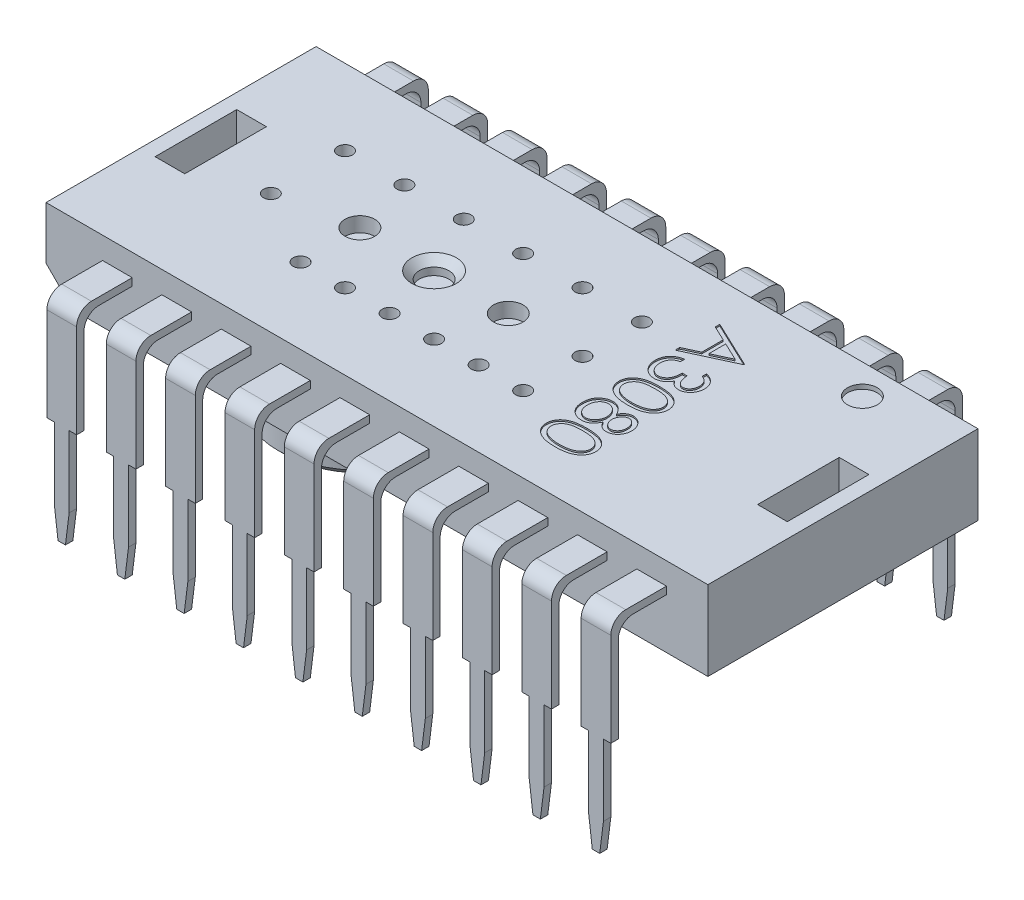
SolidWorks part; units mm, degrees
ref_plane "Front Plane" through (0, 0, 0) normal (0, 0, 1) x (1, 0, 0)
ref_plane "Top Plane" through (0, 0, 0) normal (0, 1, 0) x (1, 0, 0)
ref_plane "Right Plane" through (0, 0, 0) normal (1, 0, 0) x (0, 0, -1)
sketch "Sketch1" plane through (0, 0, 0) normal (0, 1, 0) x (1, 0, 0)
  line L1 (0, 0) -> (22.3, 0)
  line L2 (0, 0) -> (0, 9.1)
  line L3 (0, 9.1) -> (22.3, 9.1)
  line L4 (22.3, 0) -> (22.3, 9.1)
  dimension "D1" = 22.3
  dimension "D2" = 9.1
extrude "Boss-Extrude1" add sketch "Sketch1" along normal blind 3.18
sketch "Sketch2" plane through (0, 0, 0) normal (0, -1, 0) x (-1, 0, 0)
  line L0 (0, 4.55) -> (-22.3, 4.55) construction
  line L1 (0, 9.1) -> (0, 0) construction
  line L2 (-22.3, 0) -> (-22.3, 9.1) construction
  circle A0 centre (-6.025, 4.55) radius 2.8
  circle A1 centre (-6.025, 4.55) radius 0.525
  dimension "D1" = 5.6
  dimension "D3" = 1.05
  dimension "D2" = 6.025
extrude "Boss-Extrude2" add sketch "Sketch2" along normal blind 2.25 draft 1.5
chamfer "Chamfer1" distance 0.3 angle 45 1 edges at (6.025, -2.25, -7.2911)
ref_plane "Plane1" through (0, 2.19, 0) normal (0, 1, 0) x (1, 0, 0)
sketch "Sketch3" plane through (0, 2.19, 0) normal (0, 1, 0) x (1, 0, 0)
  line L0 (18.905, 9.1) -> (18.905, 10.975)
  line L1 (22.3, 9.1) -> (0, 9.1) construction
  line L2 (18.905, 10.975) -> (19.905, 10.975)
  line L3 (19.905, 10.975) -> (19.905, 9.1)
  line L4 (16.905, 9.1) -> (16.905, 10.975)
  line L5 (16.905, 10.975) -> (17.905, 10.975)
  line L6 (17.905, 10.975) -> (17.905, 9.1)
  line L7 (14.905, 9.1) -> (14.905, 10.975)
  line L8 (14.905, 10.975) -> (15.905, 10.975)
  line L9 (15.905, 10.975) -> (15.905, 9.1)
  line L10 (12.905, 9.1) -> (12.905, 10.975)
  line L11 (12.905, 10.975) -> (13.905, 10.975)
  line L12 (13.905, 10.975) -> (13.905, 9.1)
  line L13 (10.905, 9.1) -> (10.905, 10.975)
  line L14 (10.905, 10.975) -> (11.905, 10.975)
  line L15 (11.905, 10.975) -> (11.905, 9.1)
  line L16 (8.905, 9.1) -> (8.905, 10.975)
  line L17 (8.905, 10.975) -> (9.905, 10.975)
  line L18 (9.905, 10.975) -> (9.905, 9.1)
  line L19 (6.905, 9.1) -> (6.905, 10.975)
  line L20 (6.905, 10.975) -> (7.905, 10.975)
  line L21 (7.905, 10.975) -> (7.905, 9.1)
  line L22 (4.905, 9.1) -> (4.905, 10.975)
  line L23 (4.905, 10.975) -> (5.905, 10.975)
  line L24 (5.905, 10.975) -> (5.905, 9.1)
  line L25 (2.905, 9.1) -> (2.905, 10.975)
  line L26 (2.905, 10.975) -> (3.905, 10.975)
  line L27 (3.905, 10.975) -> (3.905, 9.1)
  line L28 (0.905, 9.1) -> (0.905, 10.975)
  line L29 (0.905, 10.975) -> (1.905, 10.975)
  line L30 (1.905, 10.975) -> (1.905, 9.1)
  line L31 (0, 0) -> (22.3, 0) construction
  line L32 (20.905, 0) -> (19.905, 0)
  line L33 (20.905, 0) -> (20.905, -1.875)
  line L34 (20.905, -1.875) -> (19.905, -1.875)
  line L35 (19.905, 0) -> (19.905, -1.875)
  line L36 (18.905, 0) -> (17.905, 0)
  line L37 (18.905, 0) -> (18.905, -1.875)
  line L38 (18.905, -1.875) -> (17.905, -1.875)
  line L39 (17.905, 0) -> (17.905, -1.875)
  line L40 (16.905, 0) -> (15.905, 0)
  line L41 (16.905, 0) -> (16.905, -1.875)
  line L42 (16.905, -1.875) -> (15.905, -1.875)
  line L43 (15.905, 0) -> (15.905, -1.875)
  line L44 (14.905, 0) -> (13.905, 0)
  line L45 (14.905, 0) -> (14.905, -1.875)
  line L46 (14.905, -1.875) -> (13.905, -1.875)
  line L47 (13.905, 0) -> (13.905, -1.875)
  line L48 (12.905, 0) -> (11.905, 0)
  line L49 (12.905, 0) -> (12.905, -1.875)
  line L50 (12.905, -1.875) -> (11.905, -1.875)
  line L51 (11.905, 0) -> (11.905, -1.875)
  line L52 (10.905, 0) -> (9.905, 0)
  line L53 (10.905, 0) -> (10.905, -1.875)
  line L54 (10.905, -1.875) -> (9.905, -1.875)
  line L55 (9.905, 0) -> (9.905, -1.875)
  line L56 (8.905, 0) -> (7.905, 0)
  line L57 (8.905, 0) -> (8.905, -1.875)
  line L58 (8.905, -1.875) -> (7.905, -1.875)
  line L59 (7.905, 0) -> (7.905, -1.875)
  line L60 (6.905, 0) -> (5.905, 0)
  line L61 (6.905, 0) -> (6.905, -1.875)
  line L62 (6.905, -1.875) -> (5.905, -1.875)
  line L63 (5.905, 0) -> (5.905, -1.875)
  line L64 (4.905, 0) -> (3.905, 0)
  line L65 (4.905, 0) -> (4.905, -1.875)
  line L66 (4.905, -1.875) -> (3.905, -1.875)
  line L67 (3.905, 0) -> (3.905, -1.875)
  line L68 (2.905, 0) -> (1.905, 0)
  line L69 (2.905, 0) -> (2.905, -1.875)
  line L70 (2.905, -1.875) -> (1.905, -1.875)
  line L71 (1.905, 0) -> (1.905, -1.875)
  line L72 (19.905, 9.1) -> (18.905, 9.1)
  line L73 (17.905, 9.1) -> (16.905, 9.1)
  line L74 (1.905, 9.1) -> (0.905, 9.1)
  line L75 (3.905, 9.1) -> (2.905, 9.1)
  line L76 (5.905, 9.1) -> (4.905, 9.1)
  line L77 (7.905, 9.1) -> (6.905, 9.1)
  line L78 (9.905, 9.1) -> (8.905, 9.1)
  line L79 (11.905, 9.1) -> (10.905, 9.1)
  line L80 (13.905, 9.1) -> (12.905, 9.1)
  line L81 (15.905, 9.1) -> (14.905, 9.1)
  circle A0 centre (6.025, 4.55) radius 0.525 construction
  point P6 (19.405, 10.975)
  point P51 (20.405, 0)
  dimension "D1" = 1.875
  dimension "D2" = 1
  dimension "D3" = 13.38
  dimension "D5" = 1.875
  dimension "D6" = 1
  dimension "D7" = 1
  dimension "D4" = 10
  dimension "D8" = 10
extrude "Boss-Extrude3" add sketch "Sketch3" along normal blind 0.25
sketch "Sketch5" plane through (0, 0, 1.875) normal (0, 0, 1) x (1, 0, 0)
  line L0 (2.905, 2.44) -> (1.905, 2.44) construction
  line L1 (1.905, 2.19) -> (2.905, 2.19)
  line L2 (1.905, 2.19) -> (1.905, -1.21)
  line L3 (2.155, -4.61) -> (2.655, -4.61)
  line L4 (2.905, 2.19) -> (2.905, -1.21)
  line L5 (1.905, -1.21) -> (2.155, -1.21)
  line L6 (0, 0) -> (22.3, 0) construction
  line L7 (2.405, 2.19) -> (2.405, -4.61) construction
  line L8 (2.155, -1.21) -> (2.155, -4.61)
  line L9 (2.655, -1.21) -> (2.655, -4.61)
  line L10 (2.655, -1.21) -> (2.905, -1.21)
  line L11 (3.905, 2.19) -> (4.905, 2.19)
  line L12 (3.905, 2.19) -> (3.905, -1.21)
  line L13 (4.155, -4.61) -> (4.655, -4.61)
  line L14 (4.905, 2.19) -> (4.905, -1.21)
  line L15 (3.905, -1.21) -> (4.155, -1.21)
  line L16 (4.155, -1.21) -> (4.155, -4.61)
  line L17 (4.655, -1.21) -> (4.655, -4.61)
  line L18 (4.655, -1.21) -> (4.905, -1.21)
  line L19 (4.405, 2.19) -> (4.405, -4.61) construction
  line L20 (5.905, 2.19) -> (6.905, 2.19)
  line L21 (5.905, 2.19) -> (5.905, -1.21)
  line L22 (6.155, -4.61) -> (6.655, -4.61)
  line L23 (6.905, 2.19) -> (6.905, -1.21)
  line L24 (5.905, -1.21) -> (6.155, -1.21)
  line L25 (6.155, -1.21) -> (6.155, -4.61)
  line L26 (6.655, -1.21) -> (6.655, -4.61)
  line L27 (6.655, -1.21) -> (6.905, -1.21)
  line L28 (6.405, 2.19) -> (6.405, -4.61) construction
  line L29 (7.905, 2.19) -> (8.905, 2.19)
  line L30 (7.905, 2.19) -> (7.905, -1.21)
  line L31 (8.155, -4.61) -> (8.655, -4.61)
  line L32 (8.905, 2.19) -> (8.905, -1.21)
  line L33 (7.905, -1.21) -> (8.155, -1.21)
  line L34 (8.155, -1.21) -> (8.155, -4.61)
  line L35 (8.655, -1.21) -> (8.655, -4.61)
  line L36 (8.655, -1.21) -> (8.905, -1.21)
  line L37 (8.405, 2.19) -> (8.405, -4.61) construction
  line L38 (9.905, 2.19) -> (10.905, 2.19)
  line L39 (9.905, 2.19) -> (9.905, -1.21)
  line L40 (10.155, -4.61) -> (10.655, -4.61)
  line L41 (10.905, 2.19) -> (10.905, -1.21)
  line L42 (9.905, -1.21) -> (10.155, -1.21)
  line L43 (10.155, -1.21) -> (10.155, -4.61)
  line L44 (10.655, -1.21) -> (10.655, -4.61)
  line L45 (10.655, -1.21) -> (10.905, -1.21)
  line L46 (10.405, 2.19) -> (10.405, -4.61) construction
  line L47 (11.905, 2.19) -> (12.905, 2.19)
  line L48 (11.905, 2.19) -> (11.905, -1.21)
  line L49 (12.155, -4.61) -> (12.655, -4.61)
  line L50 (12.905, 2.19) -> (12.905, -1.21)
  line L51 (11.905, -1.21) -> (12.155, -1.21)
  line L52 (12.155, -1.21) -> (12.155, -4.61)
  line L53 (12.655, -1.21) -> (12.655, -4.61)
  line L54 (12.655, -1.21) -> (12.905, -1.21)
  line L55 (12.405, 2.19) -> (12.405, -4.61) construction
  line L56 (13.905, 2.19) -> (14.905, 2.19)
  line L57 (13.905, 2.19) -> (13.905, -1.21)
  line L58 (14.155, -4.61) -> (14.655, -4.61)
  line L59 (14.905, 2.19) -> (14.905, -1.21)
  line L60 (13.905, -1.21) -> (14.155, -1.21)
  line L61 (14.155, -1.21) -> (14.155, -4.61)
  line L62 (14.655, -1.21) -> (14.655, -4.61)
  line L63 (14.655, -1.21) -> (14.905, -1.21)
  line L64 (14.405, 2.19) -> (14.405, -4.61) construction
  line L65 (15.905, 2.19) -> (16.905, 2.19)
  line L66 (15.905, 2.19) -> (15.905, -1.21)
  line L67 (16.155, -4.61) -> (16.655, -4.61)
  line L68 (16.905, 2.19) -> (16.905, -1.21)
  line L69 (15.905, -1.21) -> (16.155, -1.21)
  line L70 (16.155, -1.21) -> (16.155, -4.61)
  line L71 (16.655, -1.21) -> (16.655, -4.61)
  line L72 (16.655, -1.21) -> (16.905, -1.21)
  line L73 (16.405, 2.19) -> (16.405, -4.61) construction
  line L74 (17.905, 2.19) -> (18.905, 2.19)
  line L75 (17.905, 2.19) -> (17.905, -1.21)
  line L76 (18.155, -4.61) -> (18.655, -4.61)
  line L77 (18.905, 2.19) -> (18.905, -1.21)
  line L78 (17.905, -1.21) -> (18.155, -1.21)
  line L79 (18.155, -1.21) -> (18.155, -4.61)
  line L80 (18.655, -1.21) -> (18.655, -4.61)
  line L81 (18.655, -1.21) -> (18.905, -1.21)
  line L82 (18.405, 2.19) -> (18.405, -4.61) construction
  line L83 (19.905, 2.19) -> (20.905, 2.19)
  line L84 (19.905, 2.19) -> (19.905, -1.21)
  line L85 (20.155, -4.61) -> (20.655, -4.61)
  line L86 (20.905, 2.19) -> (20.905, -1.21)
  line L87 (19.905, -1.21) -> (20.155, -1.21)
  line L88 (20.155, -1.21) -> (20.155, -4.61)
  line L89 (20.655, -1.21) -> (20.655, -4.61)
  line L90 (20.655, -1.21) -> (20.905, -1.21)
  line L91 (20.405, 2.19) -> (20.405, -4.61) construction
  dimension "D1" = 1
  dimension "D2" = 7.05
  dimension "D3" = 1.21
  dimension "D4" = 0.25
  dimension "D5" = 0.25
  dimension "D6" = 10
extrude "Boss-Extrude4" add sketch "Sketch5" against normal blind 0.25
sketch "Sketch6" plane through (0, 0, -10.975) normal (0, 0, -1) x (-1, 0, 0)
  line L0 (-19.905, 2.19) -> (-19.905, -1.21)
  line L1 (-19.905, -1.21) -> (-19.655, -1.21)
  line L2 (-19.655, -1.21) -> (-19.655, -4.61)
  line L3 (-19.655, -4.61) -> (-19.155, -4.61)
  line L4 (-19.155, -4.61) -> (-19.155, -1.21)
  line L5 (-19.155, -1.21) -> (-18.905, -1.21)
  line L6 (-18.905, -1.21) -> (-18.905, 2.19)
  line L7 (-19.905, 2.44) -> (-18.905, 2.44) construction
  line L8 (-19.905, 2.19) -> (-18.905, 2.19)
  line L9 (-17.905, 2.19) -> (-17.905, -1.21)
  line L10 (-17.905, -1.21) -> (-17.655, -1.21)
  line L11 (-17.655, -1.21) -> (-17.655, -4.61)
  line L12 (-17.655, -4.61) -> (-17.155, -4.61)
  line L13 (-17.155, -4.61) -> (-17.155, -1.21)
  line L14 (-17.155, -1.21) -> (-16.905, -1.21)
  line L15 (-16.905, -1.21) -> (-16.905, 2.19)
  line L16 (-17.905, 2.19) -> (-16.905, 2.19)
  line L17 (-15.905, 2.19) -> (-15.905, -1.21)
  line L18 (-15.905, -1.21) -> (-15.655, -1.21)
  line L19 (-15.655, -1.21) -> (-15.655, -4.61)
  line L20 (-15.655, -4.61) -> (-15.155, -4.61)
  line L21 (-15.155, -4.61) -> (-15.155, -1.21)
  line L22 (-15.155, -1.21) -> (-14.905, -1.21)
  line L23 (-14.905, -1.21) -> (-14.905, 2.19)
  line L24 (-15.905, 2.19) -> (-14.905, 2.19)
  line L25 (-13.905, 2.19) -> (-13.905, -1.21)
  line L26 (-13.905, -1.21) -> (-13.655, -1.21)
  line L27 (-13.655, -1.21) -> (-13.655, -4.61)
  line L28 (-13.655, -4.61) -> (-13.155, -4.61)
  line L29 (-13.155, -4.61) -> (-13.155, -1.21)
  line L30 (-13.155, -1.21) -> (-12.905, -1.21)
  line L31 (-12.905, -1.21) -> (-12.905, 2.19)
  line L32 (-13.905, 2.19) -> (-12.905, 2.19)
  line L33 (-11.905, 2.19) -> (-11.905, -1.21)
  line L34 (-11.905, -1.21) -> (-11.655, -1.21)
  line L35 (-11.655, -1.21) -> (-11.655, -4.61)
  line L36 (-11.655, -4.61) -> (-11.155, -4.61)
  line L37 (-11.155, -4.61) -> (-11.155, -1.21)
  line L38 (-11.155, -1.21) -> (-10.905, -1.21)
  line L39 (-10.905, -1.21) -> (-10.905, 2.19)
  line L40 (-11.905, 2.19) -> (-10.905, 2.19)
  line L41 (-9.905, 2.19) -> (-9.905, -1.21)
  line L42 (-9.905, -1.21) -> (-9.655, -1.21)
  line L43 (-9.655, -1.21) -> (-9.655, -4.61)
  line L44 (-9.655, -4.61) -> (-9.155, -4.61)
  line L45 (-9.155, -4.61) -> (-9.155, -1.21)
  line L46 (-9.155, -1.21) -> (-8.905, -1.21)
  line L47 (-8.905, -1.21) -> (-8.905, 2.19)
  line L48 (-9.905, 2.19) -> (-8.905, 2.19)
  line L49 (-7.905, 2.19) -> (-7.905, -1.21)
  line L50 (-7.905, -1.21) -> (-7.655, -1.21)
  line L51 (-7.655, -1.21) -> (-7.655, -4.61)
  line L52 (-7.655, -4.61) -> (-7.155, -4.61)
  line L53 (-7.155, -4.61) -> (-7.155, -1.21)
  line L54 (-7.155, -1.21) -> (-6.905, -1.21)
  line L55 (-6.905, -1.21) -> (-6.905, 2.19)
  line L56 (-7.905, 2.19) -> (-6.905, 2.19)
  line L57 (-5.905, 2.19) -> (-5.905, -1.21)
  line L58 (-5.905, -1.21) -> (-5.655, -1.21)
  line L59 (-5.655, -1.21) -> (-5.655, -4.61)
  line L60 (-5.655, -4.61) -> (-5.155, -4.61)
  line L61 (-5.155, -4.61) -> (-5.155, -1.21)
  line L62 (-5.155, -1.21) -> (-4.905, -1.21)
  line L63 (-4.905, -1.21) -> (-4.905, 2.19)
  line L64 (-5.905, 2.19) -> (-4.905, 2.19)
  line L65 (-3.905, 2.19) -> (-3.905, -1.21)
  line L66 (-3.905, -1.21) -> (-3.655, -1.21)
  line L67 (-3.655, -1.21) -> (-3.655, -4.61)
  line L68 (-3.655, -4.61) -> (-3.155, -4.61)
  line L69 (-3.155, -4.61) -> (-3.155, -1.21)
  line L70 (-3.155, -1.21) -> (-2.905, -1.21)
  line L71 (-2.905, -1.21) -> (-2.905, 2.19)
  line L72 (-3.905, 2.19) -> (-2.905, 2.19)
  line L73 (-1.905, 2.19) -> (-1.905, -1.21)
  line L74 (-1.905, -1.21) -> (-1.655, -1.21)
  line L75 (-1.655, -1.21) -> (-1.655, -4.61)
  line L76 (-1.655, -4.61) -> (-1.155, -4.61)
  line L77 (-1.155, -4.61) -> (-1.155, -1.21)
  line L78 (-1.155, -1.21) -> (-0.905, -1.21)
  line L79 (-0.905, -1.21) -> (-0.905, 2.19)
  line L80 (-1.905, 2.19) -> (-0.905, 2.19)
  dimension "D1" = 3.4
  dimension "D2" = 3.4
  dimension "D3" = 7.05
  dimension "D4" = 0.25
  dimension "D5" = 0.25
  dimension "D6" = 10
extrude "Boss-Extrude5" add sketch "Sketch6" against normal blind 0.25
fillet "Fillet1" radius 0.5 40 edges at (19.405, 2.19, -10.725) (17.405, 2.19, -10.725) (15.405, 2.19, -10.725) (13.405, 2.19, -10.725) (11.405, 2.19, -10.725) (9.405, 2.19, -10.725) (7.405, 2.19, -10.725) (5.405, 2.19, -10.725) (3.405, 2.19, -10.725) (1.405, 2.19, -10.725) (18.405, 2.19, 1.625) (16.405, 2.19, 1.625) (14.405, 2.19, 1.625) (12.405, 2.19, 1.625) (10.405, 2.19, 1.625) (8.405, 2.19, 1.625) (6.405, 2.19, 1.625) (4.405, 2.19, 1.625) (2.405, 2.19, 1.625) (5.405, 2.44, -10.975) (3.405, 2.44, -10.975) (1.405, 2.44, -10.975) (7.405, 2.44, -10.975) (9.405, 2.44, -10.975) (11.405, 2.44, -10.975) (13.405, 2.44, -10.975) (15.405, 2.44, -10.975) (17.405, 2.44, -10.975) (19.405, 2.44, -10.975) (18.405, 2.44, 1.875) (16.405, 2.44, 1.875) (14.405, 2.44, 1.875) (12.405, 2.44, 1.875) (10.405, 2.44, 1.875) (8.405, 2.44, 1.875) (6.405, 2.44, 1.875) (4.405, 2.44, 1.875) (2.405, 2.44, 1.875) (20.405, 2.19, 1.625) (20.405, 2.44, 1.875)
sketch "Sketch7" plane through (0, 0, -10.975) normal (0, 0, 1) x (1, 0, 0)
  line L0 (1.53, -4.61) -> (1.655, -3.61)
  line L1 (1.655, -4.61) -> (1.155, -4.61) construction
  line L2 (1.655, -1.21) -> (1.655, -4.61) construction
  line L3 (1.28, -4.61) -> (1.155, -3.61)
  line L4 (1.155, -4.61) -> (1.155, -1.21) construction
  line L5 (1.155, -3.61) -> (1.155, -4.61)
  line L6 (1.155, -4.61) -> (1.28, -4.61)
  line L7 (1.53, -4.61) -> (1.655, -4.61)
  line L8 (1.655, -4.61) -> (1.655, -3.61)
  line L9 (2.53, -4.61) -> (2.655, -3.61)
  line L10 (2.28, -4.61) -> (2.155, -3.61)
  line L11 (2.155, -3.61) -> (2.155, -4.61)
  line L12 (2.155, -4.61) -> (2.28, -4.61)
  line L13 (2.53, -4.61) -> (2.655, -4.61)
  line L14 (2.655, -4.61) -> (2.655, -3.61)
  line L15 (3.53, -4.61) -> (3.655, -3.61)
  line L16 (3.28, -4.61) -> (3.155, -3.61)
  line L17 (3.155, -3.61) -> (3.155, -4.61)
  line L18 (3.155, -4.61) -> (3.28, -4.61)
  line L19 (3.53, -4.61) -> (3.655, -4.61)
  line L20 (3.655, -4.61) -> (3.655, -3.61)
  line L21 (4.53, -4.61) -> (4.655, -3.61)
  line L22 (4.28, -4.61) -> (4.155, -3.61)
  line L23 (4.155, -3.61) -> (4.155, -4.61)
  line L24 (4.155, -4.61) -> (4.28, -4.61)
  line L25 (4.53, -4.61) -> (4.655, -4.61)
  line L26 (4.655, -4.61) -> (4.655, -3.61)
  line L27 (5.53, -4.61) -> (5.655, -3.61)
  line L28 (5.28, -4.61) -> (5.155, -3.61)
  line L29 (5.155, -3.61) -> (5.155, -4.61)
  line L30 (5.155, -4.61) -> (5.28, -4.61)
  line L31 (5.53, -4.61) -> (5.655, -4.61)
  line L32 (5.655, -4.61) -> (5.655, -3.61)
  line L33 (6.53, -4.61) -> (6.655, -3.61)
  line L34 (6.28, -4.61) -> (6.155, -3.61)
  line L35 (6.155, -3.61) -> (6.155, -4.61)
  line L36 (6.155, -4.61) -> (6.28, -4.61)
  line L37 (6.53, -4.61) -> (6.655, -4.61)
  line L38 (6.655, -4.61) -> (6.655, -3.61)
  line L39 (7.53, -4.61) -> (7.655, -3.61)
  line L40 (7.28, -4.61) -> (7.155, -3.61)
  line L41 (7.155, -3.61) -> (7.155, -4.61)
  line L42 (7.155, -4.61) -> (7.28, -4.61)
  line L43 (7.53, -4.61) -> (7.655, -4.61)
  line L44 (7.655, -4.61) -> (7.655, -3.61)
  line L45 (8.53, -4.61) -> (8.655, -3.61)
  line L46 (8.28, -4.61) -> (8.155, -3.61)
  line L47 (8.155, -3.61) -> (8.155, -4.61)
  line L48 (8.155, -4.61) -> (8.28, -4.61)
  line L49 (8.53, -4.61) -> (8.655, -4.61)
  line L50 (8.655, -4.61) -> (8.655, -3.61)
  line L51 (9.53, -4.61) -> (9.655, -3.61)
  line L52 (9.28, -4.61) -> (9.155, -3.61)
  line L53 (9.155, -3.61) -> (9.155, -4.61)
  line L54 (9.155, -4.61) -> (9.28, -4.61)
  line L55 (9.53, -4.61) -> (9.655, -4.61)
  line L56 (9.655, -4.61) -> (9.655, -3.61)
  line L57 (10.53, -4.61) -> (10.655, -3.61)
  line L58 (10.28, -4.61) -> (10.155, -3.61)
  line L59 (10.155, -3.61) -> (10.155, -4.61)
  line L60 (10.155, -4.61) -> (10.28, -4.61)
  line L61 (10.53, -4.61) -> (10.655, -4.61)
  line L62 (10.655, -4.61) -> (10.655, -3.61)
  line L63 (11.53, -4.61) -> (11.655, -3.61)
  line L64 (11.28, -4.61) -> (11.155, -3.61)
  line L65 (11.155, -3.61) -> (11.155, -4.61)
  line L66 (11.155, -4.61) -> (11.28, -4.61)
  line L67 (11.53, -4.61) -> (11.655, -4.61)
  line L68 (11.655, -4.61) -> (11.655, -3.61)
  line L69 (12.53, -4.61) -> (12.655, -3.61)
  line L70 (12.28, -4.61) -> (12.155, -3.61)
  line L71 (12.155, -3.61) -> (12.155, -4.61)
  line L72 (12.155, -4.61) -> (12.28, -4.61)
  line L73 (12.53, -4.61) -> (12.655, -4.61)
  line L74 (12.655, -4.61) -> (12.655, -3.61)
  line L75 (13.53, -4.61) -> (13.655, -3.61)
  line L76 (13.28, -4.61) -> (13.155, -3.61)
  line L77 (13.155, -3.61) -> (13.155, -4.61)
  line L78 (13.155, -4.61) -> (13.28, -4.61)
  line L79 (13.53, -4.61) -> (13.655, -4.61)
  line L80 (13.655, -4.61) -> (13.655, -3.61)
  line L81 (14.53, -4.61) -> (14.655, -3.61)
  line L82 (14.28, -4.61) -> (14.155, -3.61)
  line L83 (14.155, -3.61) -> (14.155, -4.61)
  line L84 (14.155, -4.61) -> (14.28, -4.61)
  line L85 (14.53, -4.61) -> (14.655, -4.61)
  line L86 (14.655, -4.61) -> (14.655, -3.61)
  line L87 (15.53, -4.61) -> (15.655, -3.61)
  line L88 (15.28, -4.61) -> (15.155, -3.61)
  line L89 (15.155, -3.61) -> (15.155, -4.61)
  line L90 (15.155, -4.61) -> (15.28, -4.61)
  line L91 (15.53, -4.61) -> (15.655, -4.61)
  line L92 (15.655, -4.61) -> (15.655, -3.61)
  line L93 (16.53, -4.61) -> (16.655, -3.61)
  line L94 (16.28, -4.61) -> (16.155, -3.61)
  line L95 (16.155, -3.61) -> (16.155, -4.61)
  line L96 (16.155, -4.61) -> (16.28, -4.61)
  line L97 (16.53, -4.61) -> (16.655, -4.61)
  line L98 (16.655, -4.61) -> (16.655, -3.61)
  line L99 (17.53, -4.61) -> (17.655, -3.61)
  line L100 (17.28, -4.61) -> (17.155, -3.61)
  line L101 (17.155, -3.61) -> (17.155, -4.61)
  line L102 (17.155, -4.61) -> (17.28, -4.61)
  line L103 (17.53, -4.61) -> (17.655, -4.61)
  line L104 (17.655, -4.61) -> (17.655, -3.61)
  line L105 (18.53, -4.61) -> (18.655, -3.61)
  line L106 (18.28, -4.61) -> (18.155, -3.61)
  line L107 (18.155, -3.61) -> (18.155, -4.61)
  line L108 (18.155, -4.61) -> (18.28, -4.61)
  line L109 (18.53, -4.61) -> (18.655, -4.61)
  line L110 (18.655, -4.61) -> (18.655, -3.61)
  line L111 (19.53, -4.61) -> (19.655, -3.61)
  line L112 (19.28, -4.61) -> (19.155, -3.61)
  line L113 (19.155, -3.61) -> (19.155, -4.61)
  line L114 (19.155, -4.61) -> (19.28, -4.61)
  line L115 (19.53, -4.61) -> (19.655, -4.61)
  line L116 (19.655, -4.61) -> (19.655, -3.61)
  line L117 (20.53, -4.61) -> (20.655, -3.61)
  line L118 (20.28, -4.61) -> (20.155, -3.61)
  line L119 (20.155, -3.61) -> (20.155, -4.61)
  line L120 (20.155, -4.61) -> (20.28, -4.61)
  line L121 (20.53, -4.61) -> (20.655, -4.61)
  line L122 (20.655, -4.61) -> (20.655, -3.61)
  dimension "D1" = 0.125
  dimension "D2" = 0.125
  dimension "D3" = 1
  dimension "D4" = 1
  dimension "D5" = 20
extrude "Cut-Extrude1" cut sketch "Sketch7" along normal through all
sketch "Sketch8" plane through (0, 0, 0) normal (0, -1, 0) x (-1, 0, 0)
  line L0 (0, 4.55) -> (-22.3, 4.55) construction
  line L1 (0, 0) -> (-22.3, 0)
  line L2 (0, 0) -> (0, 9.1)
  line L3 (0, 9.1) -> (-22.3, 9.1)
  line L4 (-22.3, 0) -> (-22.3, 9.1)
  line L5 (-1.41, 0.91) -> (-20.89, 0.91)
  line L6 (-1.41, 0.91) -> (-1.41, 8.19)
  line L7 (-1.41, 8.19) -> (-20.89, 8.19)
  line L8 (-20.89, 0.91) -> (-20.89, 8.19)
  dimension "D1" = 7.28
  dimension "D2" = 3.64
  dimension "D3" = 1.41
  dimension "D4" = 0.91
  dimension "D5" = 1.41
extrude "Cut-Extrude2" cut sketch "Sketch8" against normal blind 0.5
chamfer "Chamfer2" distance 0.91 angle 45 1 edges at (0, 0.5, -4.55)
sketch "Sketch9" plane through (0, 0, 0) normal (0, -1, 0) x (-1, 0, 0)
  line L0 (-1.41, 4.55) -> (-20.89, 4.55) construction
  line L1 (-1.41, 0.91) -> (-1.41, 8.19) construction
  line L2 (-20.89, 8.19) -> (-20.89, 0.91) construction
  line L5 (-1.41, 3.05) -> (-1.41, 6.05)
  line L7 (-2.41, 4.05) -> (-2.41, 5.05)
  arc A0 (-1.41, 3.05) -> (-2.41, 4.05) centre (-1.41, 4.05) cw
  arc A1 (-1.41, 6.05) -> (-2.41, 5.05) centre (-1.41, 5.05) ccw
  point P7 (0, 0)
  point P9 (0, 0)
  point P12 (-1.4586, 4.0488)
  dimension "D4" = 1
  dimension "D3" = 0.5
  dimension "D1" = 1
  dimension "D2" = 3
extrude "Cut-Extrude3" cut sketch "Sketch9" against normal up to surface (0.5 mm away) up to face at (11.15, 0.5, -4.55)
sketch "Sketch11" plane through (0, 3.18, 0) normal (0, 1, 0) x (1, 0, 0)
  line L0 (19.405, 9.1) -> (19.405, 0) construction
  line L1 (18.905, 9.1) -> (19.905, 9.1) construction
  line L2 (0, 0) -> (22.3, 0) construction
  line L3 (22.3, 9.1) -> (0, 9.1) construction
  circle A0 centre (19.405, 8.1) radius 0.5
  dimension "D1" = 1
  dimension "D2" = 1
extrude "Cut-Extrude5" cut sketch "Sketch11" against normal blind 0.15
sketch "Sketch13" plane through (0, 3.18, 0) normal (0, 1, 0) x (1, 0, 0)
  line L0 (0, 4.55) -> (22.3, 4.55) construction
  line L1 (3.525, 6.55) -> (13.525, 6.55) construction
  line L2 (3.525, 6.55) -> (3.525, 2.55) construction
  line L3 (3.525, 2.55) -> (13.525, 2.55) construction
  line L4 (13.525, 6.55) -> (13.525, 2.55) construction
  line L5 (0, 9.1) -> (0, 0) construction
  line L6 (22.3, 0) -> (22.3, 9.1) construction
  circle A0 centre (6.025, 4.55) radius 0.5
  circle A1 centre (8.525, 4.55) radius 0.5
  circle A2 centre (11.025, 4.55) radius 0.5
  circle A3 centre (3.525, 6.55) radius 0.25
  circle A4 centre (5.525, 6.55) radius 0.25
  circle A5 centre (7.525, 6.55) radius 0.25
  circle A6 centre (9.525, 6.55) radius 0.25
  circle A7 centre (11.525, 6.55) radius 0.25
  circle A8 centre (13.525, 6.55) radius 0.25
  circle A9 centre (13.525, 4.55) radius 0.25
  circle A10 centre (13.525, 2.55) radius 0.25
  circle A11 centre (12.025, 2.55) radius 0.25
  circle A12 centre (10.525, 2.55) radius 0.25
  circle A13 centre (9.025, 2.55) radius 0.25
  circle A14 centre (7.525, 2.55) radius 0.25
  circle A15 centre (6.025, 2.55) radius 0.25
  circle A16 centre (3.525, 4.05) radius 0.25
  dimension "D1" = 1
  dimension "D5" = 2
  dimension "D6" = 5
  dimension "D7" = 5
  dimension "D8" = 0.5
  dimension "D2" = 6.025
  dimension "D4" = 2
  dimension "D3" = 3
  dimension "D9" = 6
  dimension "D10" = 3
  dimension "D11" = 6
  dimension "D12" = 2
extrude "Cut-Extrude6" cut sketch "Sketch13" against normal blind 0.5
chamfer "Chamfer3" distance 0.25 angle 45 1 edges at (8.525, 3.18, -4.05)
sketch "Sketch14" plane through (0, 3.18, 0) normal (0, 1, 0) x (1, 0, 0)
  line L0 (0, 4.55) -> (22.3, 4.55) construction
  line L1 (0, 9.1) -> (0, 0) construction
  line L2 (22.3, 0) -> (22.3, 9.1) construction
  line L3 (11.15, 9.1) -> (11.15, 0) construction
  line L4 (0.5, 5.925) -> (1.5, 5.925)
  line L5 (0.5, 5.925) -> (0.5, 3.175)
  line L6 (0.5, 3.175) -> (1.5, 3.175)
  line L7 (1.5, 5.925) -> (1.5, 3.175)
  line L8 (22.3, 9.1) -> (0, 9.1) construction
  line L9 (0, 0) -> (22.3, 0) construction
  line L10 (20.8, 5.925) -> (20.8, 3.175)
  line L11 (21.8, 3.175) -> (20.8, 3.175)
  line L12 (21.8, 5.925) -> (21.8, 3.175)
  line L13 (21.8, 5.925) -> (20.8, 5.925)
  dimension "D1" = 2.75
  dimension "D2" = 1
  dimension "D3" = 0.5
  dimension "D4" = 1.375
extrude "Cut-Extrude7" cut sketch "Sketch14" against normal blind 1
sketch "Sketch15" plane through (0, 3.18, 0) normal (0, 1, 0) x (1, 0, 0)
  line L0 (14.905, 9.1) -> (14.905, 0) construction
  line L1 (0, 0) -> (22.3, 0) construction
  text T0 "  A3080" font "Century Gothic" height in points 6
  point P6 (14.905, 9.1)
  point P7 (14.905, 9.1)
extrude "Cut-Extrude8" cut sketch "Sketch15" against normal blind 0.05
